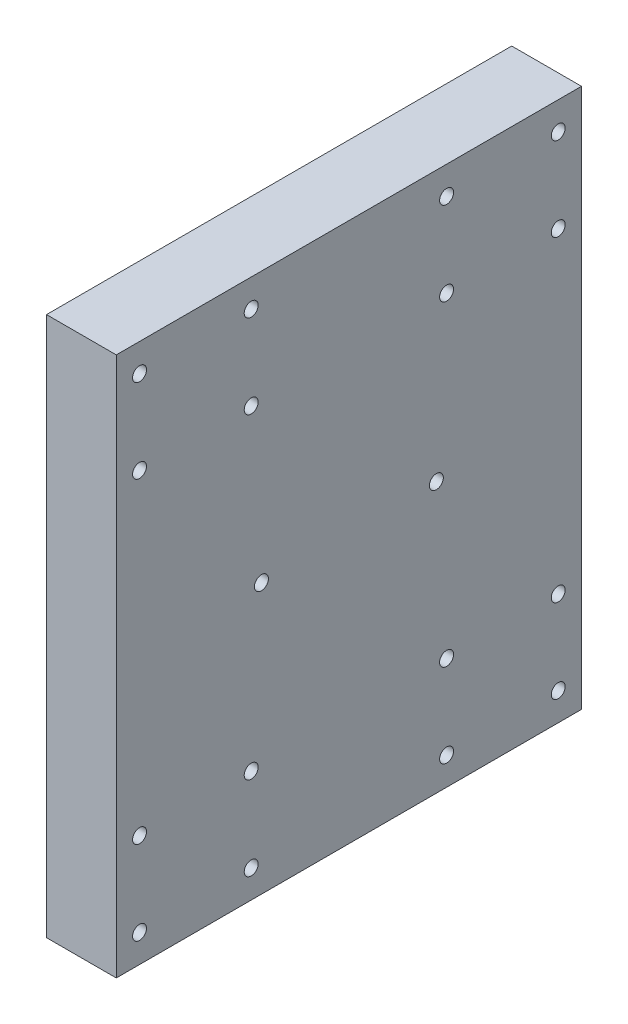
SolidWorks part; units mm, degrees
ref_plane "Alzado" through (0, 0, 0) normal (0, 0, 1) x (1, 0, 0)
ref_plane "Planta" through (0, 0, 0) normal (0, 1, 0) x (1, 0, 0)
ref_plane "Vista lateral" through (0, 0, 0) normal (1, 0, 0) x (0, 0, -1)
sketch "Croquis1" plane through (0, 0, 0) normal (1, 0, 0) x (0, 0, -1)
  line L0 (0, 58) -> (100, 58) construction
  line L1 (0, 0) -> (100, 0)
  line L2 (0, 0) -> (0, 116)
  line L3 (0, 116) -> (100, 116)
  line L4 (100, 0) -> (100, 116)
  line L5 (50, 116) -> (50, 0) construction
  circle A0 centre (5, 110) radius 1.5
  circle A1 centre (29, 110) radius 1.5
  circle A2 centre (5, 92) radius 1.5
  circle A3 centre (29, 92) radius 1.5
  circle A4 centre (5, 24) radius 1.5
  circle A5 centre (29, 24) radius 1.5
  circle A6 centre (29, 6) radius 1.5
  circle A7 centre (5, 6) radius 1.5
  circle A8 centre (31.2, 58) radius 1.5
  circle A9 centre (68.8, 58) radius 1.5
  circle A10 centre (71, 6) radius 1.5
  circle A11 centre (95, 6) radius 1.5
  circle A12 centre (95, 24) radius 1.5
  circle A13 centre (71, 24) radius 1.5
  circle A14 centre (95, 92) radius 1.5
  circle A15 centre (71, 92) radius 1.5
  circle A16 centre (71, 110) radius 1.5
  circle A17 centre (95, 110) radius 1.5
  dimension "D3" = 3
  dimension "D7" = 3
  dimension "D1" = 5
  dimension "D2" = 6
  dimension "D4" = 24
  dimension "D5" = 18
  dimension "D6" = 37.6
  dimension "D8" = 18.8
  dimension "D9" = 116
  dimension "D10" = 100
extrude "Saliente-Extruir1" add sketch "Croquis1" along normal blind 15
sketch "Croquis3" plane through (0, 0, 0) normal (-1, 0, 0) x (0, 0, 1)
  line L0 (-100, 58) -> (0, 58) construction
  line L1 (-100, 0) -> (-100, 116) construction
  line L2 (0, 116) -> (0, 0) construction
  line L3 (-53.5, 17) -> (-53.5, 58) construction
  line L4 (-53.5, 58) -> (-53.5, 99) construction
  line L5 (-100, 116) -> (0, 116) construction
  circle A0 centre (-53.5, 99) radius 5
  circle A1 centre (-53.5, 17) radius 5
  circle A2 centre (-54.5, 58) radius 11
  dimension "D1" = 10
  dimension "D6" = 22
  dimension "D2" = 17
  dimension "D3" = 53.5
  dimension "D4" = 46.5
  dimension "D5" = 1
extrude "Cortar-Extruir2" cut sketch "Croquis3" against normal blind 7
